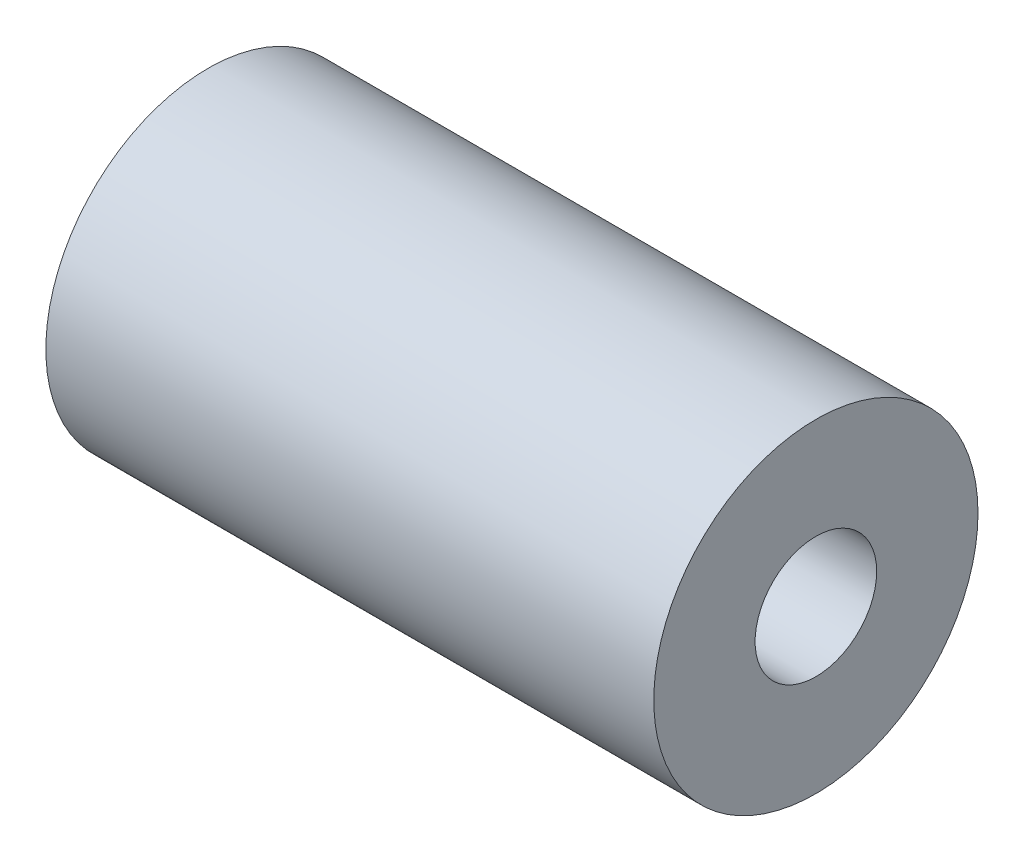
SolidWorks part; units mm, degrees
material "1060 合金"
ref_plane "正面" through (0, 0, 0) normal (0, 0, 1) x (1, 0, 0)
ref_plane "平面" through (0, 0, 0) normal (0, 1, 0) x (1, 0, 0)
ref_plane "右側面" through (0, 0, 0) normal (1, 0, 0) x (0, 0, -1)
sketch "ｽｹｯﾁ1" plane through (0, 0, 0) normal (1, 0, 0) x (0, 0, -1)
  circle A0 centre (0, 0) radius 4
  circle A1 centre (0, 0) radius 1.5
  dimension "D1" = 8
  dimension "D2" = 3
extrude "ﾎﾞｽ - 押し出し1" add sketch "ｽｹｯﾁ1" along normal blind 15
